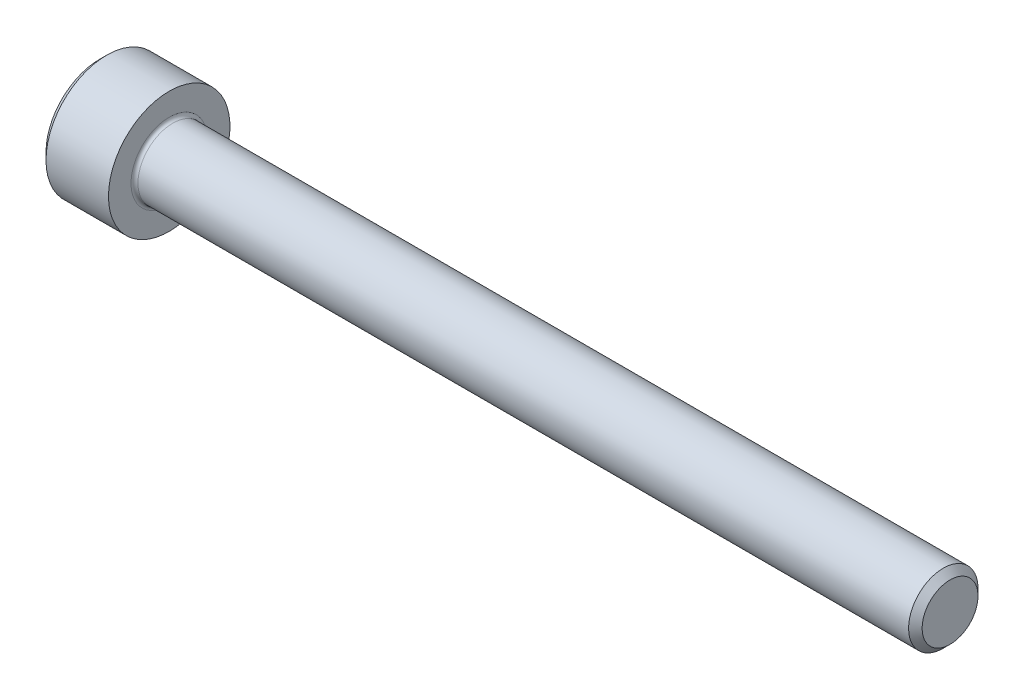
SolidWorks part; units mm, degrees
revolve "Base-Revolve" add sketch "BodySke"
sketch "BodySke" plane through (0, 0, 0) normal (0, 0, 1) x (1, 0, 0)
  line L0 (0, 0) -> (0, 3.1)
  line L1 (0.4, 3.5) -> (4, 3.5)
  line L2 (4, 3.5) -> (4, 2)
  line L3 (4, 2) -> (48.61, 2)
  line L4 (49, 1.61) -> (49, 0)
  line L5 (49, 0) -> (0, 0)
  line L6 (-31.75, 0) -> (127, 0) construction
  line L7 (0, 3.1) -> (0.4, 3.5)
  line L8 (49, 1.61) -> (48.61, 2)
  line L9 (0, -3.1) -> (0.4, -3.5) construction
  line L10 (49, -1.61) -> (48.61, -2) construction
  line L11 (4.7, 9.525) -> (4.7, 3.175) construction
  line L12 (4, 9.525) -> (4, 3.175) construction
  line L13 (-1, 9.525) -> (-1, 3.175) construction
  dimension "Diameter" = 4
  dimension "Head_ht" = 4
  dimension "Length" = 45
  dimension "Body_ch_ang" = 45
  dimension "Head_dia" = 7
  dimension "Head_ch_ang" = 45
  dimension "Minor_dia" = 3.22
  dimension "Advance" = 0.7
  dimension "Thread_nom" = 45
  dimension "Thread_length" = 50
  dimension "Head_ch_ht" = 0.4
cosmetic thread "ThreadCosmetic" [suppressed]
fillet "Fillet1" radius 0.2 1 edges at (4, 0, 2)
ref_plane "Plane1" through (0, 0, 0) normal (0, 0, 1) x (1, 0, 0)
ref_plane "Plane2" through (0, 0, 0) normal (0, 1, 0) x (1, 0, 0)
ref_plane "Plane3" through (0, 0, 0) normal (1, 0, 0) x (0, 0, -1)
other "Configuration Table"
sketch "Sketch2" plane through (0, 0, 0) normal (0, 0, 1) x (1, 0, 0)
  line L0 (0, 1.5355) -> (2, 1.5355)
  line L1 (2, 1.5355) -> (2.8865, 0)
  line L2 (-31.75, 0) -> (127, 0) construction
  line L3 (2.8865, 0) -> (0, 0)
  line L4 (0, 0) -> (0, 1.5355)
  line L5 (0, 3.1) -> (0, -3.1) construction
  line L6 (0, 0) -> (47.625, 0) construction
  line L7 (4, -3.5) -> (4, 3.5) construction
  dimension "D2" = 60
revolve "Hex-PreBroach" cut sketch "Sketch2" angle 360 about L6
sketch "Sketch3" plane through (0, 0, 0) normal (-1, 0, 0) x (0, 0.5, 0.866)
  line L0 (0.8865, 1.5355) -> (-0.8865, 1.5355)
  line L1 (-0.8865, 1.5355) -> (-1.773, 0)
  line L2 (0.8865, 1.5355) -> (1.773, 0)
  line L3 (0.8865, -1.5355) -> (1.773, 0)
  line L4 (0.8865, -1.5355) -> (-0.8865, -1.5355)
  line L5 (-0.8865, -1.5355) -> (-1.773, 0)
extrude "Hex" cut sketch "Sketch3" against normal blind 2
sketch "Sketch4" plane through (0, 0, 0) normal (-1, 0, 0) x (0, 0, 1)
  line L0 (0, 0) -> (1.7399, 0)
  line L1 (0, 0) -> (6.1484, 3.5498) construction
  line L2 (0, 0) -> (0.8699, 1.5068)
  line L3 (1.4457, 0.3947) -> (1.6607, 0.5189)
  line L4 (1.0647, 1.0546) -> (1.2797, 1.1788)
  arc A0 (1.4457, 0.3947) -> (1.0647, 1.0546) centre (0, 0) ccw
  arc A1 (1.7399, 0) -> (1.6607, 0.5189) centre (0, 0) ccw
  arc A2 (0.8699, 1.5068) -> (1.2797, 1.1788) centre (0, 0) cw
  dimension "D1" = 30
  dimension "D2" = 60
extrude "Spline" [suppressed] cut sketch "Sketch4" against normal blind 2
pattern_circular "CirPattern1" [suppressed] count 6 every 60
sketch "Sketch5" plane through (0, 0, 0) normal (0, 0, 1) x (1, 0, 0)
  line L0 (-31.75, 0) -> (127, 0) construction
  line L2 (0, 3.1) -> (0, -3.1) construction
  circle A0 centre (1.6, 0) radius 0.675
  dimension "Drilled_hole_dia" = 1.35
  dimension "Drilled_hole_loc" = 1.6
extrude "Hole" [suppressed] cut sketch "Sketch5" against normal through all and the other way through all
pattern_circular "Drilled-4" [suppressed] count 2 every 60
pattern_circular "Drilled-6" [suppressed] count 3 every 60
sketch "ThdSchSke" plane through (0, 0, 0) normal (0, 0, 1) x (1, 0, 0)
  line L0 (4.7, -1.61) -> (4.4269, -2)
  line L1 (4.7, -1.61) -> (4.9731, -2)
  line L2 (4.9731, -2) -> (4.9731, -2.5)
  line L3 (-3.175, 0) -> (5.1513, 0) construction
  line L5 (4.9731, -2.5) -> (4.4269, -2.5)
  line L6 (4.4269, -2.5) -> (4.4269, -2)
  line L7 (0, 3.1) -> (0, -3.1) construction
revolve "ThreadSchematic" [suppressed] cut sketch "ThdSchSke" angle 360 about L3
pattern_linear "ThdSchPat" [suppressed]
equation "\"D2@Sketch3\" = \"Hex_size@Sketch3\" / 2"
equation "\"D1@Sketch3\" = \"Hex_size@Sketch3\" / 2"
equation "\"D1@Sketch2\" = \"Hex_size@Sketch3\" / 2"
equation "\"D3@Sketch4\" = \"Spline_p_dim@Sketch4\" / 2"
equation "\"Thread_minor@ThreadCosmetic\"  =  \"Minor_dia@BodySke\""
equation "\"D2@CirPattern1\" = 360 / \"Num_teeth@CirPattern1\""
equation "\"Wall_thickness@Sketch2\" = \"Head_ht@BodySke\" - \"Key_eng@Hex\""
equation "\"Thread_length@ThreadCosmetic\" = ((sgn( (\"Length@BodySke\" - \"Advance@BodySke\" ) - \"Thread_nom@BodySke\" )-1)*( (\"Length@BodySke\" - \"Advance@BodySke\" ) - \"Thread_nom@BodySke\" ))/-2+ \"Thread_nom@BodySke\""
equation "\"Thread_minor@ThdSchSke\" = \"Minor_dia@BodySke\""
equation "\"Diameter@ThdSchSke\" = \"Diameter@BodySke\""
equation "\"Overcut@ThdSchSke\" = \"Diameter@BodySke\" * 1.25"
equation "\"Start@ThdSchSke\" = \"Head_ht@BodySke\" + \"Length@BodySke\" - \"Thread_length@ThreadCosmetic\"  '---Non-countersunk---"
equation "\"Num_threads@ThdSchPat\" = int( \"Thread_length@ThreadCosmetic\" / \"Advance@BodySke\" + 0.999 )  + 1"
equation "\"Advance@ThdSchPat\" = \"Thread_length@ThreadCosmetic\" /  (\"Num_threads@ThdSchPat\" - 1) 'relax it"
equation "\"Num_threads@ThdSchPat\" = \"Num_threads@ThdSchPat\" - sgn( \"Num_threads@ThdSchPat\" - 1) '---chamfered tips only---"
